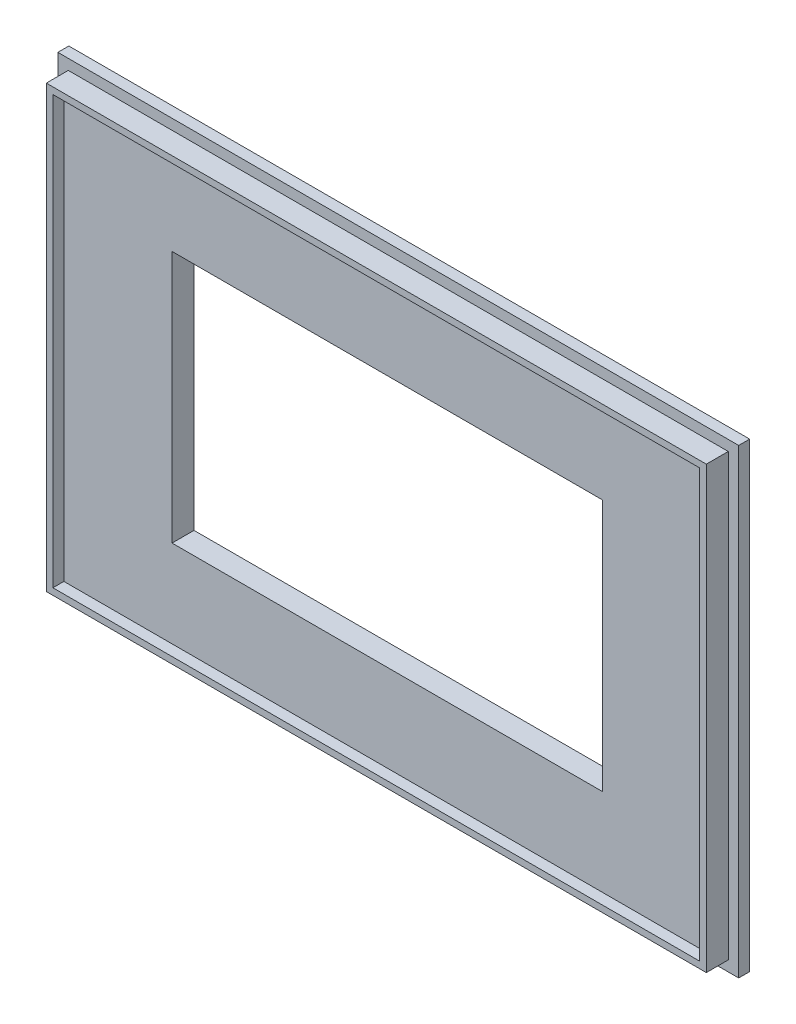
SolidWorks part; units mm, degrees
ref_plane "Front Plane" through (0, 0, 0) normal (0, 0, 1) x (1, 0, 0)
ref_plane "Top Plane" through (0, 0, 0) normal (0, 1, 0) x (1, 0, 0)
ref_plane "Right Plane" through (0, 0, 0) normal (1, 0, 0) x (0, 0, -1)
sketch "Sketch1" plane through (0, 0, 0) normal (0, 0, 1) x (1, 0, 0)
  line L1 (-78.74, -53.34) -> (78.74, -53.34)
  line L2 (-78.74, -53.34) -> (-78.74, 53.34)
  line L3 (-78.74, 53.34) -> (78.74, 53.34)
  line L4 (78.74, -53.34) -> (78.74, 53.34)
  line L5 (-78.74, -53.34) -> (78.74, 53.34) construction
  line L6 (-78.74, 53.34) -> (78.74, -53.34) construction
  point P0 (0, 0)
  dimension "D1" = 157.48
  dimension "D2" = 106.68
extrude "Boss-Extrude1" add sketch "Sketch1" along normal blind 2.54
sketch "Sketch2" plane through (0, 0, 2.54) normal (0, 0, 1) x (1, 0, 0)
  line L1 (-76.327, -50.927) -> (76.327, -50.927)
  line L2 (-76.327, -50.927) -> (-76.327, 50.927)
  line L3 (-76.327, 50.927) -> (76.327, 50.927)
  line L4 (76.327, -50.927) -> (76.327, 50.927)
  line L5 (-76.327, -50.927) -> (76.327, 50.927) construction
  line L6 (-76.327, 50.927) -> (76.327, -50.927) construction
  point P0 (0, 0)
  dimension "D1" = 152.654
  dimension "4.01in" = 101.854
extrude "Boss-Extrude2" add sketch "Sketch2" along normal blind 5.08 contours L2 L1 L4 L3
sketch "Sketch3" plane through (0, 0, 7.62) normal (0, 0, 1) x (1, 0, 0)
  line L1 (-74.803, -49.403) -> (74.803, -49.403)
  line L2 (-74.803, -49.403) -> (-74.803, 49.403)
  line L3 (-74.803, 49.403) -> (74.803, 49.403)
  line L4 (74.803, -49.403) -> (74.803, 49.403)
  line L5 (-74.803, -49.403) -> (74.803, 49.403) construction
  line L6 (-74.803, 49.403) -> (74.803, -49.403) construction
  point P0 (0, 0)
  dimension "D1" = 149.606
  dimension "D2" = 98.806
extrude "Cut-Extrude1" cut sketch "Sketch3" against normal blind 2.54
sketch "Sketch4" plane through (0, 0, 5.08) normal (0, 0, 1) x (1, 0, 0)
  line L1 (-49.784, -29.21) -> (49.784, -29.21)
  line L2 (-49.784, -29.21) -> (-49.784, 29.21)
  line L3 (-49.784, 29.21) -> (49.784, 29.21)
  line L4 (49.784, -29.21) -> (49.784, 29.21)
  line L5 (-49.784, -29.21) -> (49.784, 29.21) construction
  line L6 (-49.784, 29.21) -> (49.784, -29.21) construction
  point P0 (0, 0)
  dimension "D1" = 99.568
  dimension "D2" = 58.42
extrude "Cut-Extrude2" cut sketch "Sketch4" against normal through all
